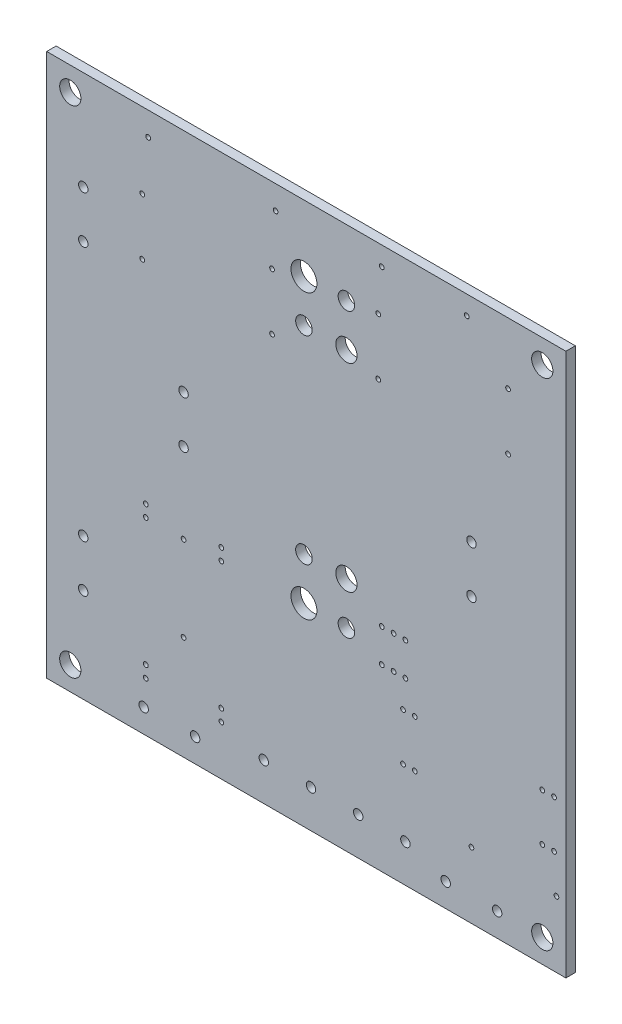
SolidWorks part; units mm, degrees
ref_plane "Спереди" through (0, 0, 0) normal (0, 0, 1) x (1, 0, 0)
ref_plane "Сверху" through (0, 0, 0) normal (0, 1, 0) x (1, 0, 0)
ref_plane "Справа" through (0, 0, 0) normal (1, 0, 0) x (0, 0, -1)
sketch "Эскиз1" plane through (0, 0, 0) normal (0, 0, 1) x (1, 0, 0)
  line L0 (0, -28.2487) -> (0, 39.6717) construction
  line L1 (-51.0947, 0) -> (41.8328, 0) construction
  line L3 (-55, -57.5) -> (55, -57.5)
  line L4 (-55, -57.5) -> (-55, 57.5)
  line L5 (-55, 57.5) -> (55, 57.5)
  line L6 (55, -57.5) -> (55, 57.5)
  circle A0 centre (-50, 52.5) radius 2.25
  circle A1 centre (50, 52.5) radius 2.25
  circle A2 centre (50, -52.5) radius 2.25
  circle A3 centre (-50, -52.5) radius 2.25
  dimension "D3" = 5
  dimension "D5" = 4.5
  dimension "D1" = 110
  dimension "D2" = 115
  dimension "D4" = 5
extrude "Вытянуть1" add sketch "Эскиз1" along normal blind 2
sketch "Эскиз2" plane through (0, 0, 2) normal (0, 0, 1) x (1, 0, 0)
  line L0 (29.55, -52.5) -> (40.45, -52.5) construction
  line L1 (-34.45, -52.5) -> (-23.55, -52.5) construction
  line L2 (-55, -57.5) -> (55, -57.5) construction
  line L3 (-55, 57.5) -> (-55, -57.5) construction
  line L4 (-55, -57.5) -> (55, -57.5) construction
  line L5 (-34, -44.5) -> (-34, -5.1445) construction
  line L6 (-28.7644, -49.5) -> (30.142, -49.5) construction
  line L7 (-34, -44.5) -> (-13.7421, -44.5) construction
  line L8 (-18, -44.5) -> (-18, -5.2439) construction
  line L9 (23, -35.5) -> (62.3364, -35.5) construction
  line L10 (23, -25.5) -> (62.7631, -25.5) construction
  line L11 (-33.5, 52.5) -> (14.1525, 52.5) construction
  circle A0 centre (-47.25, -37.5) radius 1
  circle A1 centre (-47.25, -27.5) radius 1
  circle A2 centre (-47.25, 26.5) radius 1
  circle A3 centre (-47.25, 36.5) radius 1
  circle A4 centre (29.55, -52.5) radius 1
  circle A5 centre (40.45, -52.5) radius 1
  circle A6 centre (-34.45, -52.5) radius 1
  circle A7 centre (-23.55, -52.5) radius 1
  circle A8 centre (-34, -44.5) radius 0.5
  circle A9 centre (-34, -17.5) radius 0.5
  circle A10 centre (-18, -44.5) radius 0.5
  circle A11 centre (-18, -17.5) radius 0.5
  circle A12 centre (-34, -47) radius 0.5
  circle A13 centre (-9, -49.5) radius 1
  circle A14 centre (1, -49.5) radius 1
  circle A15 centre (11, -49.5) radius 1
  circle A16 centre (21, -49.5) radius 1
  circle A17 centre (-34, -15) radius 0.5
  circle A18 centre (-18, -15) radius 0.5
  circle A19 centre (-18, -47) radius 0.5
  circle A20 centre (23, -35.5) radius 0.5
  circle A21 centre (50, -35.5) radius 0.5
  circle A22 centre (20.5, -35.5) radius 0.5
  circle A23 centre (52.5, -35.5) radius 0.5
  circle A24 centre (23, -25.5) radius 0.5
  circle A25 centre (50, -25.5) radius 0.5
  circle A26 centre (20.5, -25.5) radius 0.5
  circle A27 centre (52.5, -25.5) radius 0.5
  circle A28 centre (-33.5, 52.5) radius 0.5
  circle A29 centre (-6.5, 52.5) radius 0.5
  dimension "D4" = 46
  dimension "D5" = 10
  dimension "D6" = 7.75
  dimension "D10" = 7.75
  dimension "D11" = 7.75
  dimension "D12" = 7.75
  dimension "D13" = 10.9
  dimension "D15" = 84.55
  dimension "D17" = 10.9
  dimension "D18" = 5
  dimension "D19" = 2
  dimension "D21" = 10
  dimension "D22" = 10
  dimension "D23" = 20
  dimension "D27" = 2.5
  dimension "D33" = 40
  dimension "D34" = 2.5
  dimension "D36" = 27
  dimension "D39" = 2.5
  dimension "D40" = 2.5
  dimension "D41" = 10
  dimension "D42" = 75.5
  dimension "D43" = 27
  dimension "D44" = 27
  dimension "D46" = 110
  dimension "D25" = 27
  dimension "D8" = 20
  dimension "D16" = 2
  dimension "D31" = 27
  dimension "D3" = 8
  dimension "D7" = 10
  dimension "D9" = 84
  dimension "D14" = 5
  dimension "D20" = 20.55
  dimension "D24" = 16
  dimension "D26" = 2.5
  dimension "D28" = 2.5
  dimension "D29" = 2.5
  dimension "D30" = 21
  dimension "D32" = 40
  dimension "D35" = 2.5
  dimension "D37" = 22
  dimension "D38" = 75.5
  dimension "D45" = 21.5
extrude "Вырез-Вытянуть1" cut sketch "Эскиз2" against normal blind 2
sketch "Эскиз3" plane through (0, 0, 2) normal (0, 0, 1) x (1, 0, 0)
  line L0 (8.5, 43.5) -> (8.5, 34.5) construction
  line L1 (8.5, 34.5) -> (-0.5, 34.5) construction
  line L2 (-20.263, 13.5) -> (26.1332, 13.5) construction
  line L3 (-55, 57.5) -> (-55, -57.5) construction
  line L4 (-55, -57.5) -> (55, -57.5) construction
  line L5 (-26, -0.5) -> (-26, 9.5) construction
  line L6 (35, 2.5) -> (35, 12.5) construction
  line L7 (16, -19.5) -> (21, -19.5) construction
  line L8 (18.5, -19.5) -> (18.5, -13) construction
  line L9 (16, -12.5) -> (21, -12.5) construction
  line L10 (-26, -35.5) -> (-26, -17.5) construction
  line L11 (35, -43.5) -> (53, -43.5) construction
  line L12 (16, 53.5) -> (34, 53.5) construction
  circle A0 centre (-26, 9.5) radius 1
  circle A1 centre (-26, -0.5) radius 1
  circle A2 centre (-0.5, 34.5) radius 1.75
  circle A3 centre (-0.5, 43.5) radius 2.75
  circle A4 centre (8.5, 43.5) radius 1.75
  circle A5 centre (8.5, 34.5) radius 2.25
  circle A6 centre (8.5, -16.5) radius 1.75
  circle A7 centre (8.5, -7.5) radius 2.25
  circle A8 centre (-0.5, -16.5) radius 2.75
  circle A9 centre (-0.5, -7.5) radius 1.75
  circle A10 centre (35, 12.5) radius 1
  circle A11 centre (35, 2.5) radius 1
  circle A12 centre (21, -19.5) radius 0.5
  circle A13 centre (18.5, -19.5) radius 0.5
  circle A14 centre (16, -19.5) radius 0.5
  circle A15 centre (21, -12.5) radius 0.5
  circle A16 centre (18.5, -12.5) radius 0.5
  circle A17 centre (16, -12.5) radius 0.5
  circle A18 centre (-26, -35.5) radius 0.5
  circle A19 centre (-26, -17.5) radius 0.5
  circle A20 centre (35, -43.5) radius 0.5
  circle A21 centre (53, -43.5) radius 0.5
  circle A22 centre (16, 53.5) radius 0.5
  circle A23 centre (34, 53.5) radius 0.5
  dimension "D4" = 9
  dimension "D5" = 9
  dimension "D6" = 9
  dimension "D10" = 30
  dimension "D11" = 54.5
  dimension "D12" = 101
  dimension "D13" = 54.5
  dimension "D15" = 29
  dimension "D17" = 10
  dimension "D18" = 60
  dimension "D19" = 90
  dimension "D21" = 5
  dimension "D22" = 1
  dimension "D23" = 38
  dimension "D27" = 22
  dimension "D33" = 18
  dimension "D34" = 71
  dimension "D25" = 45
  dimension "D2" = 3.5
  dimension "D1" = 5.5
  dimension "D9" = 4.5
  dimension "D3" = 3.5
  dimension "D7" = 9
  dimension "D20" = 2
  dimension "D26" = 18
  dimension "D29" = 1
  dimension "D8" = 9
  dimension "D14" = 10
  dimension "D16" = 57
  dimension "D24" = 76
  dimension "D28" = 29
  dimension "D30" = 18
  dimension "D31" = 14
  dimension "D32" = 90
  dimension "D35" = 111
extrude "Вырез-Вытянуть2" cut sketch "Эскиз3" against normal blind 2
sketch "Эскиз4" plane through (0, 0, 2) normal (0, 0, 1) x (1, 0, 0)
  line L1 (-34.75, 29.5) -> (-7.25, 29.5) construction
  line L2 (-34.75, 29.5) -> (-34.75, 41.5) construction
  line L4 (-55, 57.5) -> (-55, -57.5) construction
  line L5 (-55, -57.5) -> (55, -57.5) construction
  line L6 (15.25, 32.5) -> (42.75, 32.5) construction
  line L7 (15.25, 32.5) -> (15.25, 44.5) construction
  circle A0 centre (15.25, 32.5) radius 0.5
  circle A1 centre (42.75, 32.5) radius 0.5
  circle A2 centre (15.25, 44.5) radius 0.5
  circle A3 centre (42.75, 44.5) radius 0.5
  circle A8 centre (-34.75, 29.5) radius 0.5
  circle A9 centre (-7.25, 29.5) radius 0.5
  circle A10 centre (-34.75, 41.5) radius 0.5
  circle A11 centre (-7.25, 41.5) radius 0.5
  dimension "D3" = 12
  dimension "D4" = 20.25
  dimension "D7" = 27.5
  dimension "D9" = 70.25
  dimension "D13" = 27.5
  dimension "D14" = 27.5
  dimension "D2" = 1
  dimension "D10" = 12
  dimension "D5" = 87
  dimension "D6" = 27.5
  dimension "D8" = 90
extrude "Вырез-Вытянуть3" cut sketch "Эскиз4" against normal blind 10
